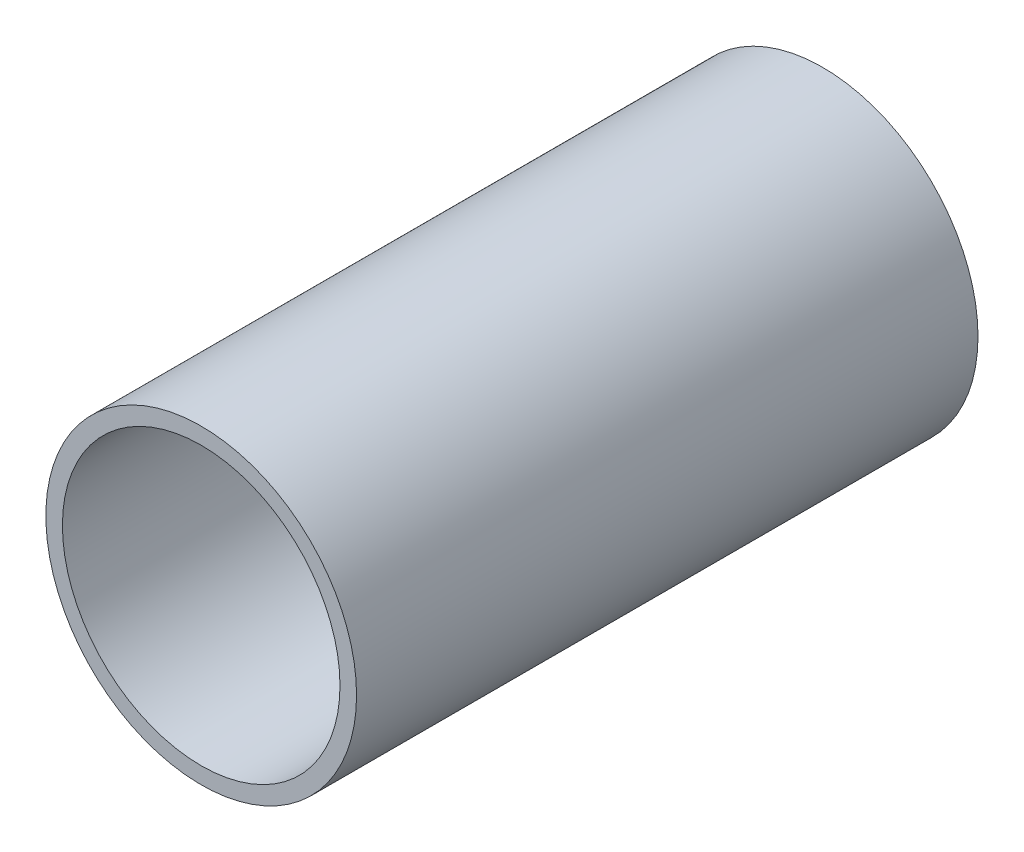
SolidWorks part; units mm, degrees
ref_plane "Front Plane" through (0, 0, 0) normal (0, 0, 1) x (1, 0, 0)
ref_plane "Top Plane" through (0, 0, 0) normal (0, 1, 0) x (1, 0, 0)
ref_plane "Right Plane" through (0, 0, 0) normal (1, 0, 0) x (0, 0, -1)
sketch "Sketch1" plane through (0, 0, 0) normal (0, 0, 1) x (1, 0, 0)
  circle A0 centre (0, 0) radius 13.4
  circle A1 centre (0, 0) radius 15
  dimension "D1" = 26.8
  dimension "D2" = 30
extrude "Boss-Extrude1" add sketch "Sketch1" along normal blind 60
